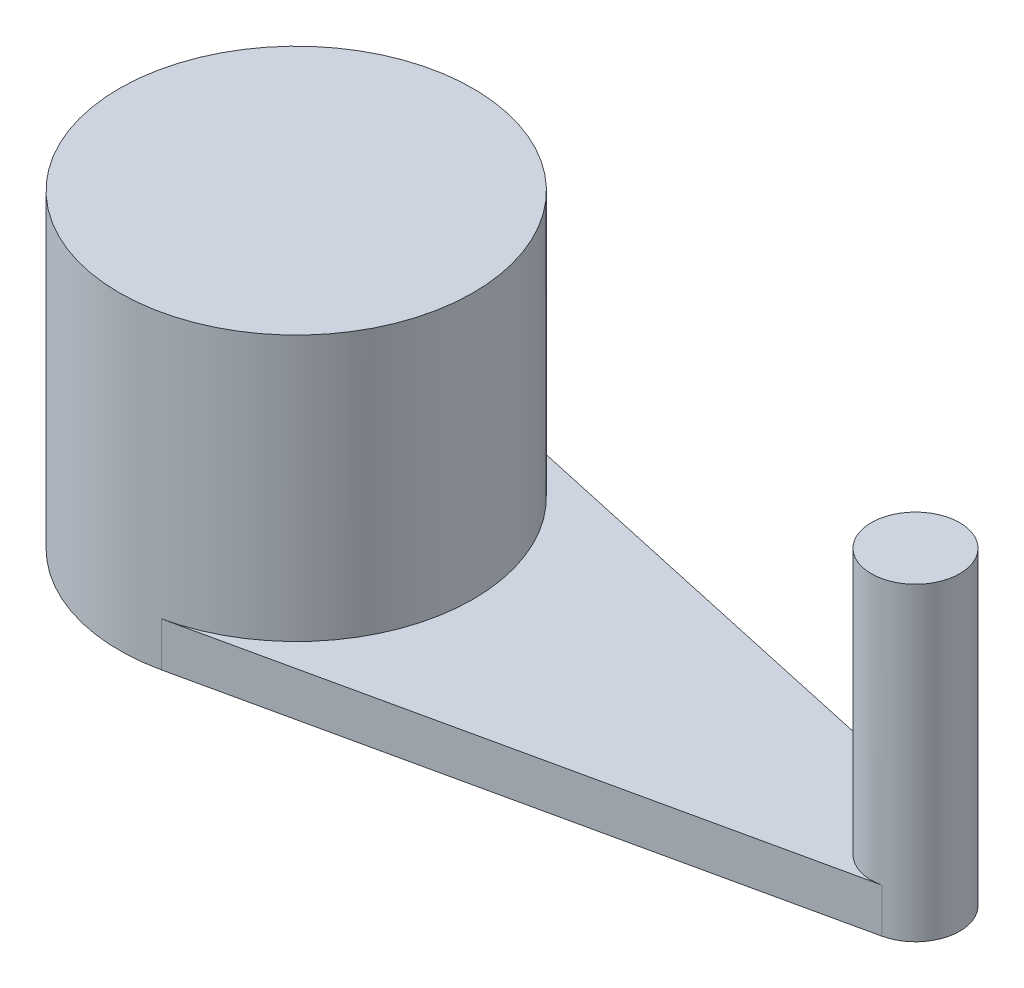
SolidWorks part; units mm, degrees
ref_plane "前视基准面" through (0, 0, 0) normal (0, 0, 1) x (1, 0, 0)
ref_plane "上视基准面" through (0, 0, 0) normal (0, 1, 0) x (1, 0, 0)
ref_plane "右视基准面" through (0, 0, 0) normal (1, 0, 0) x (0, 0, -1)
other "Configuration Table"
sketch "草图1" plane through (0, 0, 0) normal (0, 1, 0) x (1, 0, 0)
  line L0 (0, 0) -> (70, 0)
  line L1 (1.9621, 20.0452) -> (71.0714, 4.8839)
  line L2 (1.9621, -20.0452) -> (71.0714, -4.8839)
  circle A0 centre (0, 0) radius 20
  circle A1 centre (70, 0) radius 5
  point P7 (71.0617, 4.886)
  point P8 (0, 0)
  point P9 (0, 0)
  dimension "D1" = 40
  dimension "D3" = 10
  dimension "D4" = 5
  dimension "D2" = 70
extrude "凸台-拉伸1" add sketch "草图1" along normal blind 5
sketch "草图2" plane through (0, 5, 0) normal (0, 1, 0) x (1, 0, 0)
  circle A0 centre (0, 0) radius 20
  circle A1 centre (70, 0) radius 5
extrude "凸台-拉伸2" add sketch "草图2" along normal blind 30
